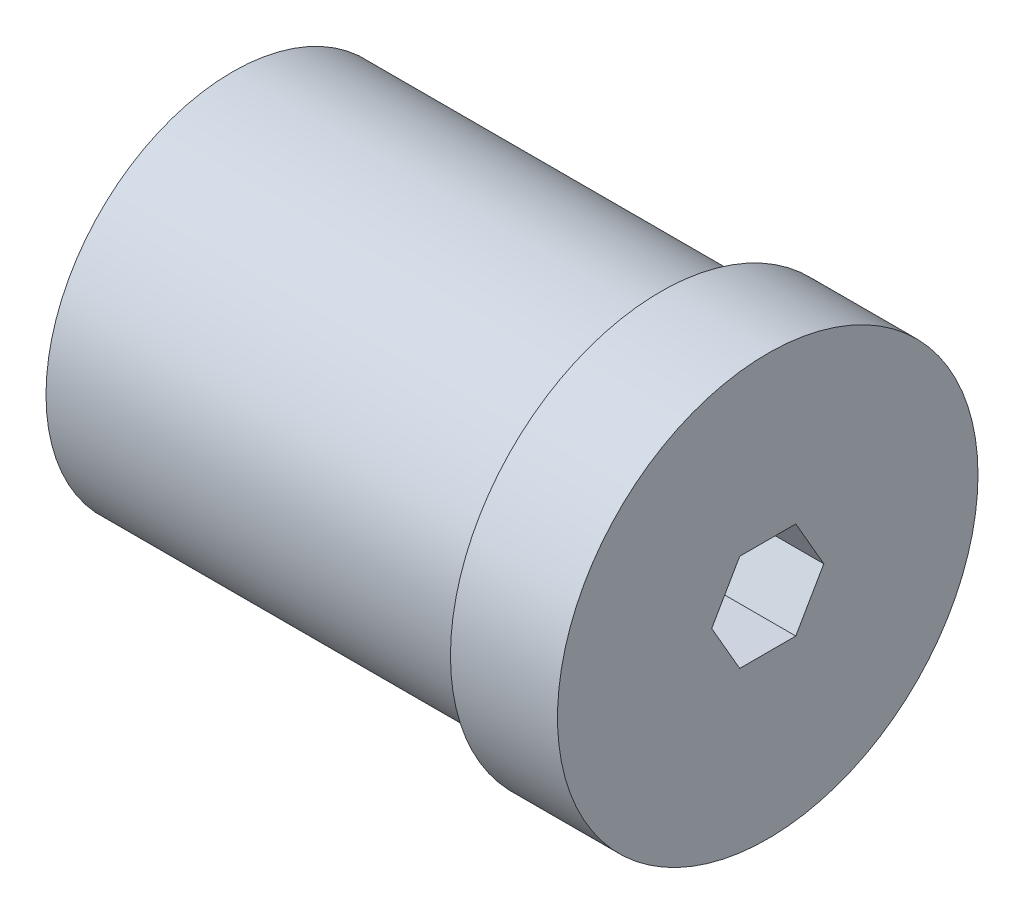
SolidWorks part; units mm, degrees
ref_plane "Alzado" through (0, 0, 0) normal (0, 0, 1) x (1, 0, 0)
ref_plane "Planta" through (0, 0, 0) normal (0, 1, 0) x (1, 0, 0)
ref_plane "Vista lateral" through (0, 0, 0) normal (1, 0, 0) x (0, 0, -1)
sketch "Croquis1" plane through (0, 0, 0) normal (1, 0, 0) x (0, 0, -1)
  line L1 (7.3323, 0) -> (3.6662, 6.35)
  line L2 (3.6662, 6.35) -> (-3.6662, 6.35)
  line L3 (-3.6662, 6.35) -> (-7.3323, 0)
  line L4 (-7.3323, 0) -> (-3.6662, -6.35)
  line L5 (-3.6662, -6.35) -> (3.6662, -6.35)
  line L6 (3.6662, -6.35) -> (7.3323, 0)
  circle A0 centre (0, 0) radius 24.4
  circle A1 centre (0, 0) radius 6.35 construction
  dimension "D1" = 48.8
  dimension "D2" = 12.7
extrude "Saliente-Extruir1" add sketch "Croquis1" along normal blind 70
sketch "Croquis2" plane through (70, 0, 0) normal (1, 0, 0) x (0, 0, -1)
  circle A0 centre (0, 0) radius 24.4
  circle A1 centre (0, 0) radius 27.5
  dimension "D1" = 55
extrude "Saliente-Extruir2" add sketch "Croquis2" against normal blind 4
sketch "Croquis3" plane through (66, 0, 0) normal (-1, 0, 0) x (0, 0, 1)
  circle A0 centre (0, 0) radius 27.5
  circle A1 centre (0, 0) radius 25.4
  circle A2 centre (0, 0) radius 27.5 construction
  dimension "D1" = 50.8
extrude "Saliente-Extruir3" add sketch "Croquis3" along normal blind 10
